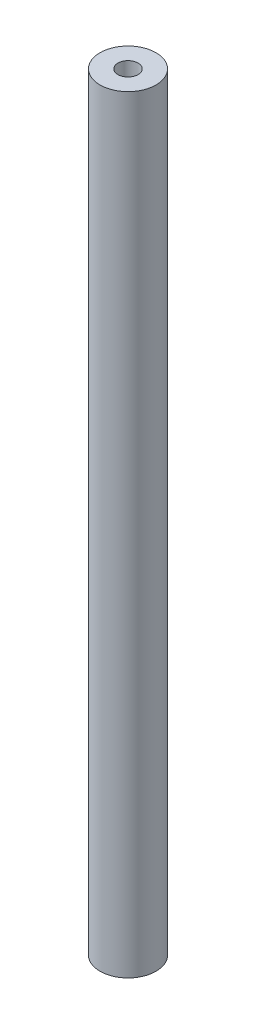
SolidWorks part; units mm, degrees
ref_plane "Front Plane" through (0, 0, 0) normal (0, 0, 1) x (1, 0, 0)
ref_plane "Top Plane" through (0, 0, 0) normal (0, 1, 0) x (1, 0, 0)
ref_plane "Right Plane" through (0, 0, 0) normal (1, 0, 0) x (0, 0, -1)
sketch "Sketch1" plane through (0, 0, 0) normal (0, 1, 0) x (1, 0, 0)
  circle A0 centre (0, 0) radius 5.5562
  dimension "D1" = 11.1125
extrude "Boss-Extrude1" add sketch "Sketch1" along normal blind 152.4
sketch "Sketch2" plane through (0, 152.4, 0) normal (0, 1, 0) x (1, 0, 0)
  circle A0 centre (0, 0) radius 2
  dimension "D1" = 4
extrude "Cut-Extrude1" cut sketch "Sketch2" against normal blind 7
sketch "Sketch3" plane through (0, 0, 0) normal (0, -1, 0) x (1, 0, 0)
  circle A0 centre (0, 0) radius 2
  dimension "D1" = 4
extrude "Cut-Extrude2" cut sketch "Sketch3" against normal blind 7
